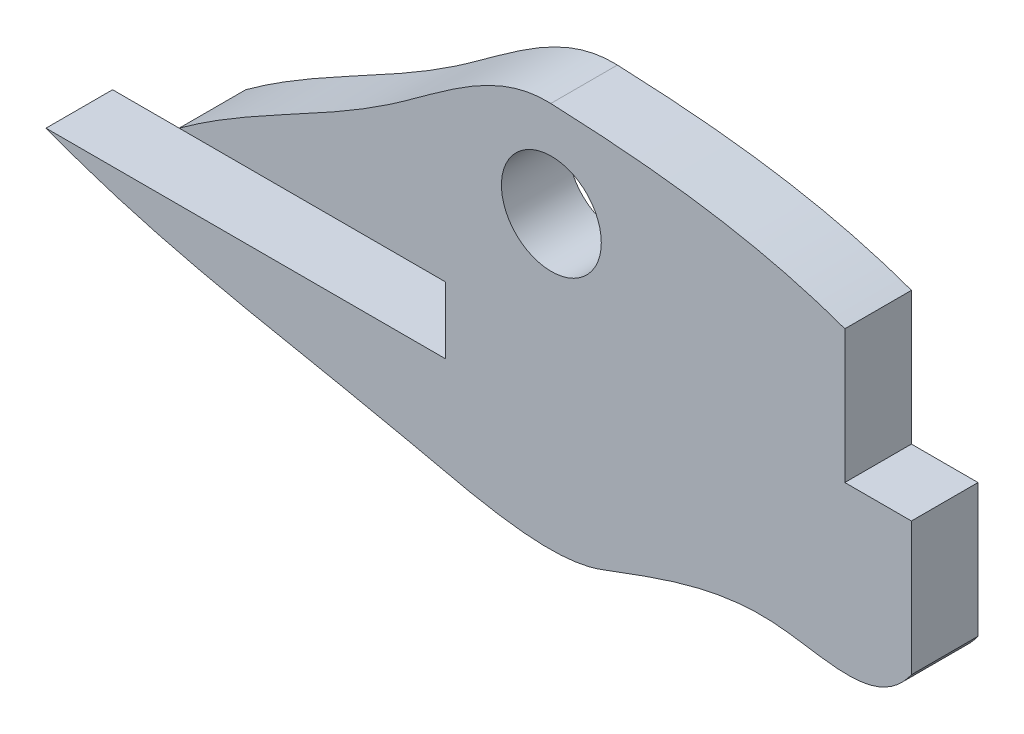
SolidWorks part; units mm, degrees
ref_plane "Front Plane" through (0, 0, 0) normal (0, 0, 1) x (1, 0, 0)
ref_plane "Top Plane" through (0, 0, 0) normal (0, 1, 0) x (1, 0, 0)
ref_plane "Right Plane" through (0, 0, 0) normal (1, 0, 0) x (0, 0, -1)
sketch "Sketch1" plane through (0, 0, 0) normal (0, 0, 1) x (1, 0, 0)
  line L0 (-19.05, 0) -> (0, 0)
  line L1 (0, 0) -> (0, 3.175)
  line L2 (0, 3.175) -> (-12.7, 3.175)
  circle A0 centre (5.0484, 8.5101) radius 2.3813
  spline S0 degree 3 poles (-19.05, 0) (-13.112, -2.2773) (-5.1558, -3.2046) (8.2173, -6.7744) (12.0309, 0.9319) (12.9312, 8.2593) (4.8164, 15.37) (-3.5923, 7.7856) (-9.2154, 5.719) (-12.7, 3.175) knots 0 0 0 0 0.256909 0.405238 0.477393 0.591318 0.708775 0.830232 1 1 1 1
  dimension "D4" = 4.7625
  dimension "D1" = 19.05
  dimension "D2" = 12.7
  dimension "D3" = 3.175
extrude "Boss-Extrude1" add sketch "Sketch1" along normal blind 3.175
sketch "Sketch2" plane through (0, 0, 3.175) normal (0, 0, 1) x (1, 0, 0)
  line L0 (4.9882, 13.0567) -> (8.4797, 10.1337)
  line L1 (9.5181, 10.7616) -> (19.0431, 10.7616)
  line L2 (9.5181, 10.7616) -> (9.5181, -1.9384)
  line L3 (9.5181, -1.9384) -> (22.2181, -1.9384)
  line L4 (22.2181, 4.4116) -> (22.2181, -1.9384)
  line L5 (8.4797, 10.1337) -> (7.5693, -4.9353)
  line L9 (22.2181, 4.4116) -> (19.0431, 4.4116)
  line L10 (19.0431, 10.7616) -> (19.0431, 4.4116)
  spline S0 degree 3 poles (-19.05, 0) (-13.112, -2.2773) (-5.1558, -3.2046) (8.2173, -6.7744) (12.0309, 0.9319) (12.9312, 8.2593) (4.8164, 15.37) (-3.5923, 7.7856) (-9.2154, 5.719) (-12.7, 3.175) knots 0 0 0 0 0.256909 0.405238 0.477393 0.591318 0.708775 0.830232 1 1 1 1 construction
  spline S1 degree 3 poles (7.5693, -4.9353) (10.1774, -3.9731) (15.151, -1.9687) (20.5326, -4.3075) (22.2181, -1.9384) knots 0 0 0 0 0.552836 1 1 1 1
  spline S2 degree 3 poles (4.9882, 13.0567) (9.7187, 12.8599) (14.5594, 12.3893) (19.0431, 10.7616) knots 0 0 0 0 1 1 1 1
  spline M5 degree 3 poles (-19.05, 0) (-13.112, -2.2773) (-5.1558, -3.2046) (8.2173, -6.7744) (12.0309, 0.9319) (12.9312, 8.2593) (4.8164, 15.37) (-3.5923, 7.7856) (-9.2154, 5.719) (-12.7, 3.175) knots 0 0 0 0 0.256909 0.405238 0.477393 0.591318 0.708775 0.830232 1 1 1 1
  dimension "D1" = 12.7
  dimension "D2" = 12.7
  dimension "D3" = 3.175
  dimension "D4" = 6.35
extrude "Boss-Extrude2" add sketch "Sketch2" against normal blind 3.175 contours S2 L1 M5 | L5 S1 L3 L2 L0 M5 | L10 L1 L3 L4 L9 M5 | L2 L3 M5 | S1 L3 M5
